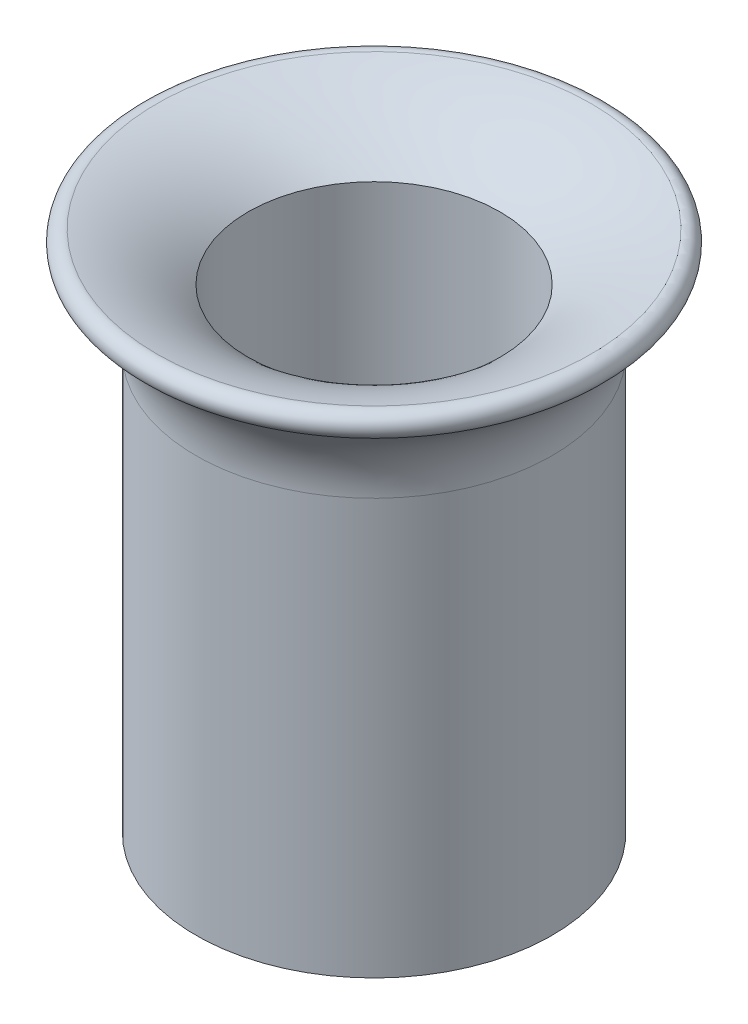
SolidWorks part; units mm, degrees
ref_plane "Front Plane" through (0, 0, 0) normal (0, 0, 1) x (1, 0, 0)
ref_plane "Top Plane" through (0, 0, 0) normal (0, 1, 0) x (1, 0, 0)
ref_plane "Right Plane" through (0, 0, 0) normal (1, 0, 0) x (0, 0, -1)
sketch "Sketch1" plane through (0, 0, 0) normal (0, 0, 1) x (1, 0, 0)
  line L4 (0, 0) -> (30, 0)
  line L5 (30, 0) -> (30, 80)
  line L6 (30, 80) -> (8.8887, 80)
  line L7 (0, 70.0119) -> (0, 0)
  line L8 (0, 35.0059) -> (0, 70.0119) construction
  line L9 (8.8887, 80) -> (8.7668, 80)
  arc A0 (0, 70.0119) -> (-8.0815, 84.4846) centre (-17, 70.0119) ccw
  arc A1 (-6.5778, 88.135) -> (8.7668, 80) centre (-14.3029, 55.0242) cw
  arc A2 (-8.0815, 84.4846) -> (-6.5778, 88.135) centre (-7.0323, 86.1873) cw
  dimension "D1" = 80
  dimension "D3" = 17
  dimension "D4" = 2
  dimension "D2" = 30
revolve "Revolve2" add sketch "Sketch1" angle 360 about L5
sketch "Sketch3" plane through (0, 80, 0) normal (0, 1, 0) x (1, 0, 0)
  circle A1 centre (30, 0) radius 21.2332
  circle A2 centre (30, 0) radius 21.2332
  dimension "D1" = 0
extrude "Cut-Extrude1" cut sketch "Sketch3" against normal blind 70
